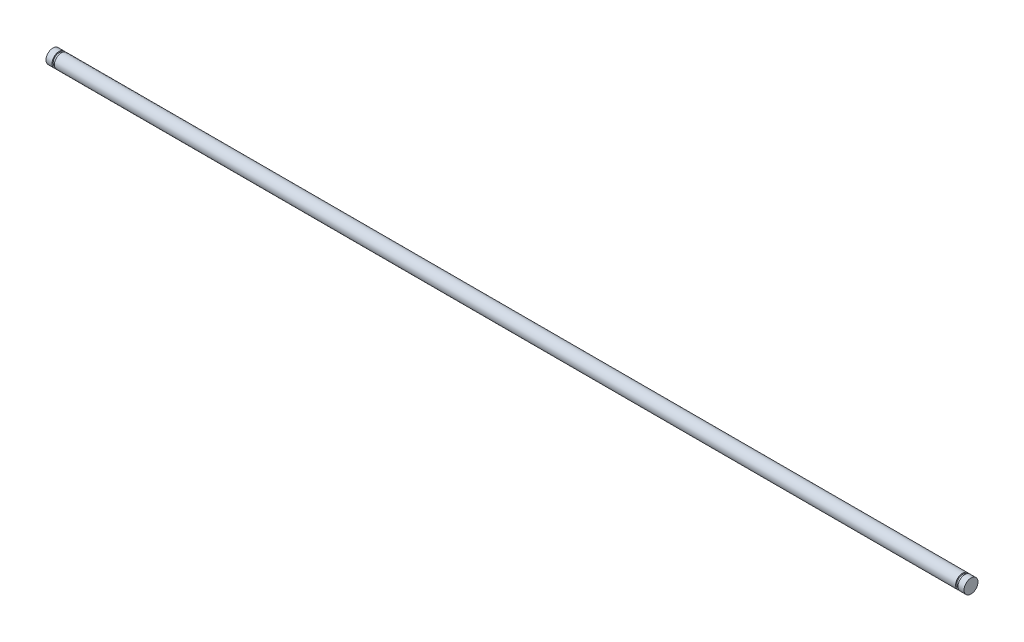
SolidWorks part; units mm, degrees
material "Plain Carbon Steel"
ref_plane "Front Plane" through (0, 0, 0) normal (0, 0, 1) x (1, 0, 0)
ref_plane "Top Plane" through (0, 0, 0) normal (0, 1, 0) x (1, 0, 0)
ref_plane "Right Plane" through (0, 0, 0) normal (1, 0, 0) x (0, 0, -1)
sketch "Sketch1" plane through (0, 0, 0) normal (1, 0, 0) x (0, 0, -1)
  circle A0 centre (0, 0) radius 1.5
  dimension "D1" = 3
extrude "Boss-Extrude1" add sketch "Sketch1" along normal blind 197 contours A0
ref_axis "Axis1" through (197, 0, 0) along (-1, 0, 0)
sketch "Sketch2" plane through (0, 0, 0) normal (0, 0, 1) x (1, 0, 0)
  line L0 (197, 1.5) -> (0, 1.5) construction
  line L1 (1.3, 1.5) -> (1.8, 1.5)
  line L2 (1.3, 1.5) -> (1.3, 1.25)
  line L3 (1.3, 1.25) -> (1.8, 1.25)
  line L4 (1.8, 1.5) -> (1.8, 1.25)
  line L5 (0, 1.5) -> (0, -1.5) construction
  dimension "D1" = 0.5
  dimension "D2" = 0.25
  dimension "D3" = 1.3
revolve "Cut-Revolve1" cut sketch "Sketch2" angle 360 about axis through (197, 0, 0) along (-1, 0, 0)
ref_plane "Plane2" through (98.5, 0, 0) normal (-1, 0, 0) x (0, 0, 1)
mirror "Mirror1" about plane through (98.5, 0, 0) normal (-1, 0, 0) of "Cut-Revolve1"
